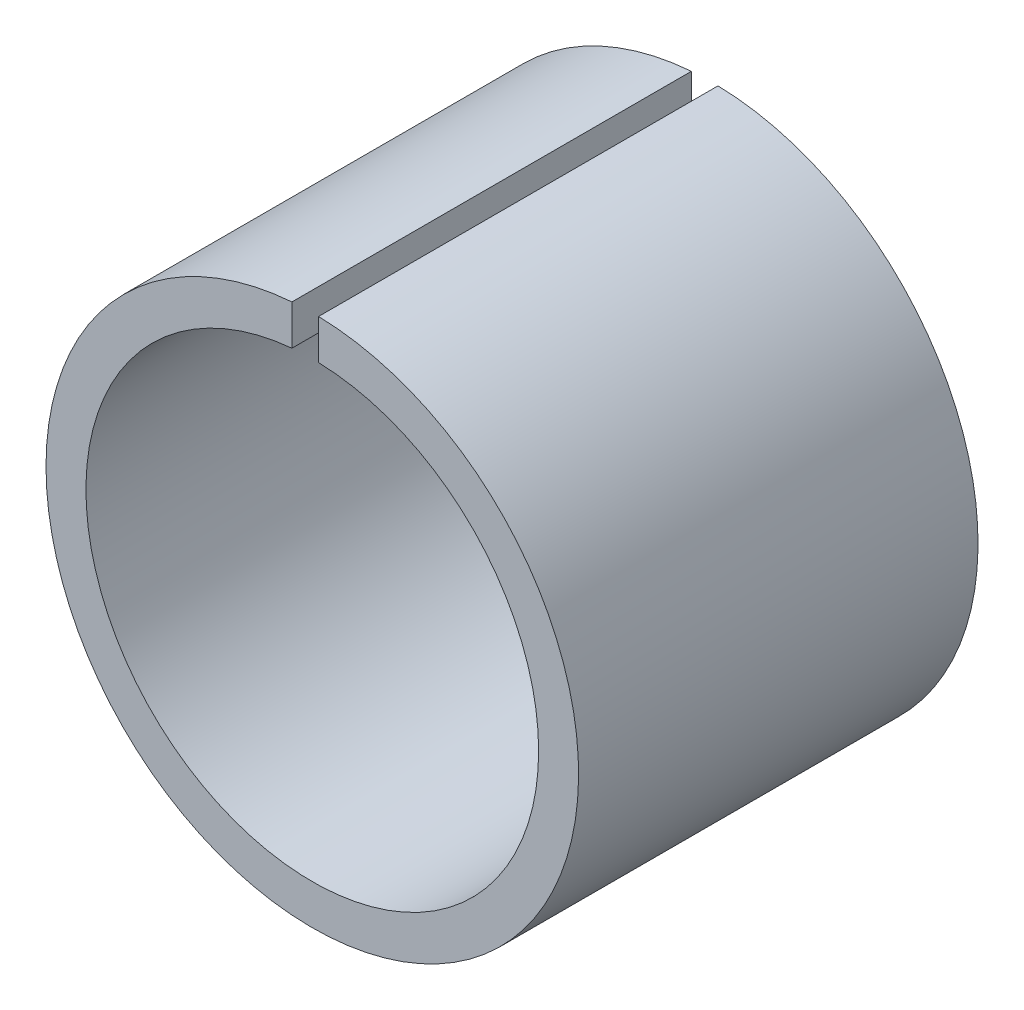
SolidWorks part; units mm, degrees
material "AISI 1020"
ref_plane "Front" through (0, 0, 0) normal (0, 0, 1) x (1, 0, 0)
ref_plane "Top" through (0, 0, 0) normal (0, 1, 0) x (1, 0, 0)
ref_plane "Right" through (0, 0, 0) normal (1, 0, 0) x (0, 0, -1)
sketch "Sketch1" plane through (0, 0, 0) normal (0, 0, 1) x (1, 0, 0)
  circle A0 centre (0, 0) radius 10
  dimension "D1" = 20
extrude "Boss-Extrude1" add sketch "Sketch1" along normal blind 15
sketch "Sketch3" plane through (0, 0, 15) normal (0, 0, 1) x (1, 0, 0)
  circle A0 centre (0, 0) radius 8.5
  dimension "D1" = 17
extrude "Cut-Extrude1" cut sketch "Sketch3" against normal blind 19
ref_plane "Plane2" through (0, 8, 0) normal (0, 1, 0) x (1, 0, 0)
sketch "Sketch4" plane through (0, 8, 0) normal (0, 1, 0) x (1, 0, 0)
  line L0 (-0.7653, 0) -> (0.2347, 0)
  line L1 (8.5, 0) -> (-8.5, 0) construction
  line L2 (10, 0) -> (-10, 0) construction
  line L3 (0.2347, 0) -> (0.2347, -15)
  line L4 (-10, -15) -> (10, -15) construction
  line L5 (0.2347, -15) -> (-0.7653, -15)
  line L6 (-0.7653, -15) -> (-0.7653, 0)
  dimension "D1" = 1
extrude "Cut-Extrude3" cut sketch "Sketch4" along normal blind 3
